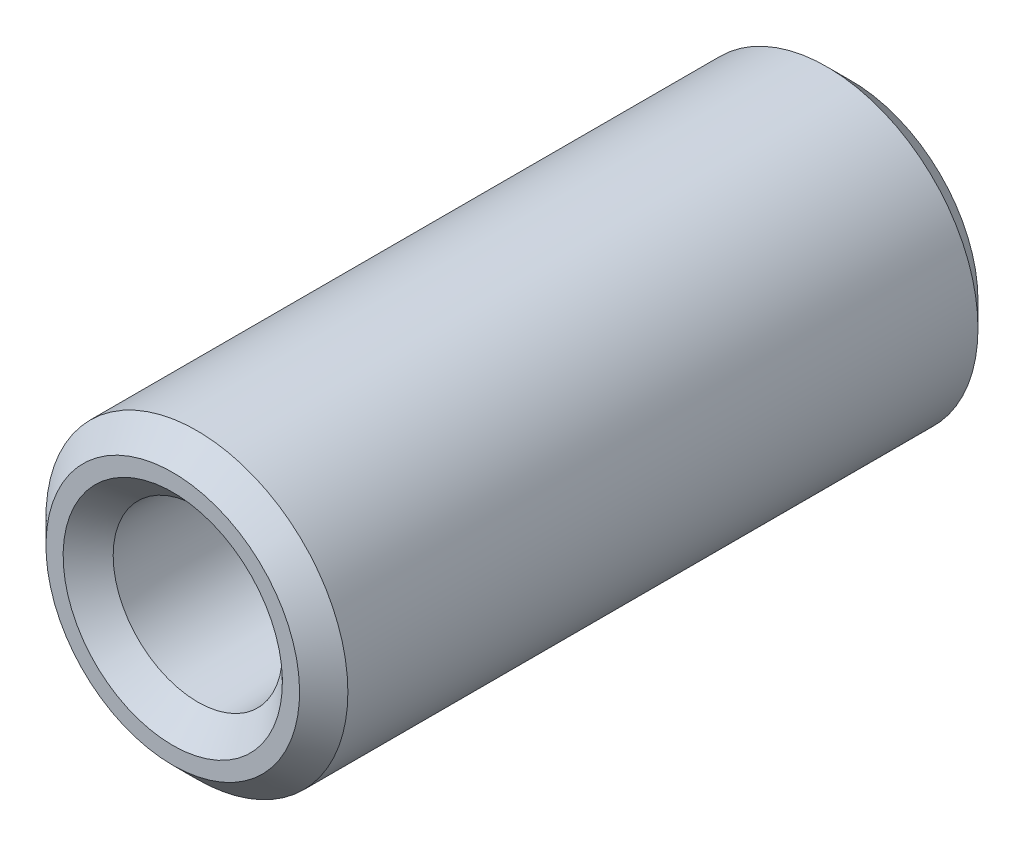
SolidWorks part; units mm, degrees
material "PET"
ref_plane "Front Plane" through (0, 0, 0) normal (0, 0, 1) x (1, 0, 0)
ref_plane "Top Plane" through (0, 0, 0) normal (0, 1, 0) x (1, 0, 0)
ref_plane "Right Plane" through (0, 0, 0) normal (1, 0, 0) x (0, 0, -1)
sketch "Sketch1" plane through (0, 0, 0) normal (0, 0, 1) x (1, 0, 0)
  circle A0 centre (0, 6.0097) radius 1.3
  circle A1 centre (0, 6.0097) radius 3.175
  dimension "D1" = 2.6
  dimension "D2" = 6.35
extrude "Boss-Extrude1" add sketch "Sketch1" along normal up to surface (14.2687 mm away)
draft "Draft2" type of draft neutral plane draft angle 2 faces to draft 1 face at (1.3, 6.0097, 0) neutral plane through (0, 6.0097, 0) neutral plane normal (0, 0, -1) reverse direction yes parameters "D1"=2
chamfer "Chamfer1" distance 0.508 angle 45 3 edges at (3.175, 6.0097, 0) (0, 4.2114, 14.2687) (0, 2.8347, 14.2687)
